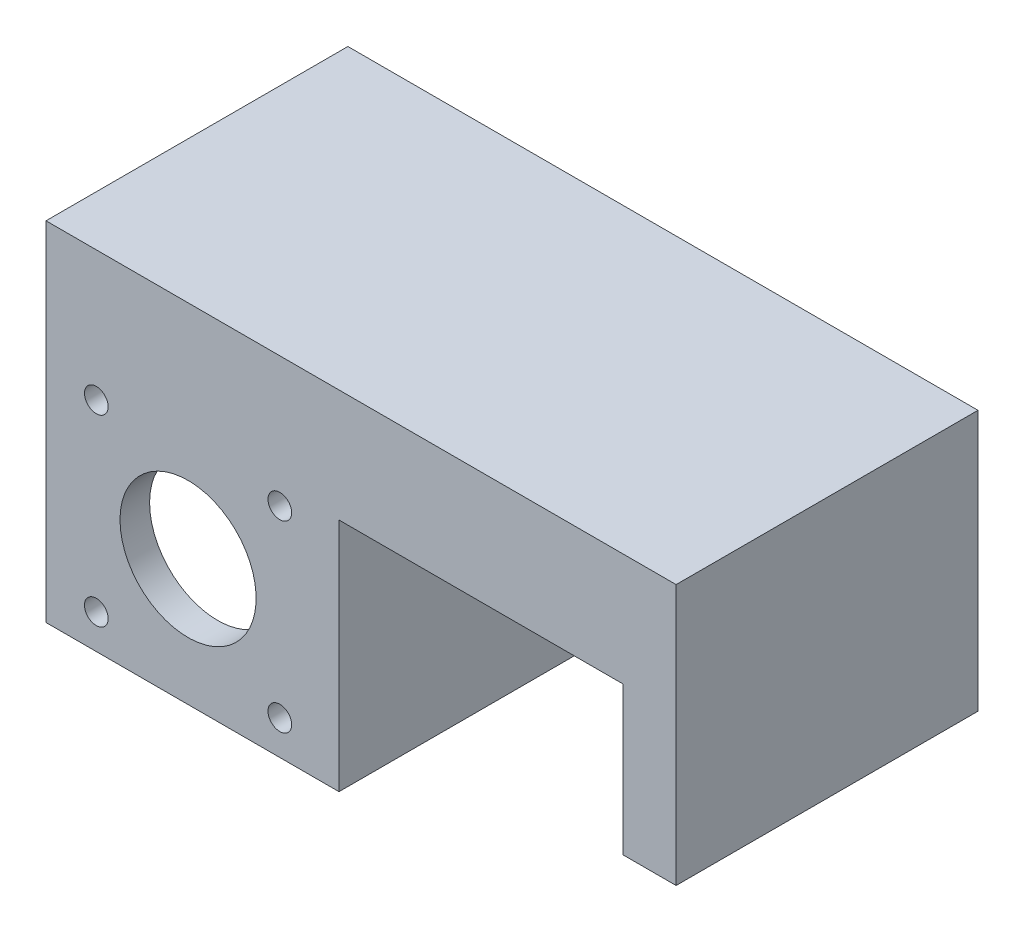
SolidWorks part; units mm, degrees
ref_plane "Front Plane" through (0, 0, 0) normal (0, 0, 1) x (1, 0, 0)
ref_plane "Top Plane" through (0, 0, 0) normal (0, 1, 0) x (1, 0, 0)
ref_plane "Right Plane" through (0, 0, 0) normal (1, 0, 0) x (0, 0, -1)
sketch "Sketch1" plane through (0, 0, 0) normal (0, 0, 1) x (1, 0, 0)
  line L1 (0, 0) -> (48, 0)
  line L2 (0, 0) -> (0, 53)
  line L3 (0, 53) -> (48, 53)
  line L4 (48, 0) -> (48, 53)
  dimension "D1" = 53
  dimension "D2" = 48
extrude "Boss-Extrude1" add sketch "Sketch1" along normal blind 10
sketch "Sketch2" plane through (0, 0, 0) normal (0, 0, -1) x (-1, 0, 0)
  line L0 (0, 53) -> (0, 0) construction
  line L1 (-48, 0) -> (0, 0)
  line L2 (-48, 0) -> (-48, -5.6163)
  line L3 (-48, -5.6163) -> (0, -5.6163)
  line L4 (0, 0) -> (0, -5.6163)
  dimension "D1" = 5.6163
extrude "Boss-Extrude2" add sketch "Sketch2" against normal blind 33.1918
sketch "Sketch4" plane through (0, 0, 10) normal (0, 0, 1) x (1, 0, 0)
  line L1 (0, 53) -> (4, 53)
  line L2 (0, 53) -> (0, 43)
  line L3 (0, 43) -> (4, 43)
  line L4 (4, 53) -> (4, 43)
  line L5 (48, 53) -> (44, 53)
  line L6 (48, 53) -> (48, 43)
  line L7 (48, 43) -> (44, 43)
  line L8 (44, 53) -> (44, 43)
  dimension "D1" = 10
  dimension "D2" = 4
extrude "Boss-Extrude4" add sketch "Sketch4" along normal blind 40
sketch "Sketch5" plane through (0, 0, 10) normal (0, 0, 1) x (1, 0, 0)
  line L0 (48, 0) -> (48, 43) construction
  line L1 (0, 0) -> (48, 0)
  line L2 (0, 0) -> (0, 10.8609)
  line L3 (0, 10.8609) -> (48, 10.8609)
  line L4 (48, 0) -> (48, 10.8609)
  dimension "D1" = 10.8609
extrude "Boss-Extrude5" add sketch "Sketch5" along normal up to surface (23.1918 mm away) up to face at (24, -2.8082, 33.1918)
sketch "Sketch6" plane through (0, -5.6163, 0) normal (0, -1, 0) x (1, 0, 0)
  line L0 (0, 0) -> (0, 28.1918) construction
  line L1 (0, 33.1918) -> (0, 0) construction
  line L2 (48, 33.1918) -> (48, 0) construction
  line L3 (0, 28.1918) -> (48, 28.1918)
  line L4 (0, 28.1918) -> (0, 33.1918)
  line L5 (0, 33.1918) -> (48, 33.1918)
  line L6 (48, 28.1918) -> (48, 33.1918)
  line L8 (48, 33.1918) -> (0, 33.1918) construction
  dimension "D2" = 5
extrude "Boss-Extrude6" add sketch "Sketch6" along normal blind 42.3
sketch "Sketch7" plane through (0, 0, 0) normal (-1, 0, 0) x (0, 0, 1)
  line L0 (33.1918, 10.8609) -> (10, 10.8609) construction
  line L1 (0, -5.6163) -> (-12.8082, -5.6163)
  line L2 (0, -5.6163) -> (0, 10.8609)
  line L3 (0, 10.8609) -> (-12.8082, 10.8609)
  line L4 (-12.8082, -5.6163) -> (-12.8082, 10.8609)
  line L5 (28.1918, -47.9163) -> (28.1918, -5.6163) construction
  dimension "D1" = 41
extrude "Boss-Extrude7" add sketch "Sketch7" against normal up to surface (48 mm away) up to face at (48, 10.6657, 24.2767)
sketch "Sketch8" plane through (0, 0, 28.1918) normal (0, 0, -1) x (-1, 0, 0)
  line L0 (-24, -26.6163) -> (-24, -5.6163) construction
  line L1 (0, -5.6163) -> (-48, -5.6163) construction
  line L3 (-8.5, -42.1163) -> (-39.5, -42.1163) construction
  line L4 (-8.5, -42.1163) -> (-8.5, -11.1163) construction
  line L5 (-8.5, -11.1163) -> (-39.5, -11.1163) construction
  line L6 (-39.5, -42.1163) -> (-39.5, -11.1163) construction
  line L7 (-8.5, -42.1163) -> (-39.5, -11.1163) construction
  line L8 (-8.5, -11.1163) -> (-39.5, -42.1163) construction
  circle A0 centre (-24, -26.6163) radius 11.5
  circle A1 centre (-39.5, -11.1163) radius 2
  circle A2 centre (-39.5, -42.1163) radius 2
  circle A3 centre (-8.5, -11.1163) radius 2
  circle A4 centre (-8.5, -42.1163) radius 2
  dimension "D2" = 23
  dimension "D4" = 4
  dimension "D1" = 21
  dimension "D3" = 31
extrude "Cut-Extrude1" cut sketch "Sketch8" against normal up to next
fillet "Fillet1" radius 10 1 edges at (24, 10.8609, 0)
fillet "Fillet2" radius 4 2 edges at (2, 43, 10) (46, 43, 10)
sketch "Sketch9" plane through (48, 0, 0) normal (1, 0, 0) x (0, 0, -1)
  line L1 (12.8082, 10.8609) -> (17.8082, 10.8609)
  line L2 (12.8082, 10.8609) -> (12.8082, -5.6163)
  line L3 (12.8082, -5.6163) -> (17.8082, -5.6163)
  line L4 (17.8082, 10.8609) -> (17.8082, -5.6163)
  line L5 (-28.1918, -5.6163) -> (12.8082, -5.6163) construction
  dimension "D1" = 5
extrude "Boss-Extrude9" add sketch "Sketch9" against normal up to surface (48 mm away) contours L4 L3 L2 L1 up to face at (0, 13.3569, 15.8852)
sketch "Sketch10" plane through (48, 0, 0) normal (1, 0, 0) x (0, 0, -1)
  line L0 (17.8082, 10.8609) -> (-33.1918, 10.8609)
  line L1 (-33.1918, 10.8609) -> (-76.8871, 43.9021)
  line L2 (-76.8871, 43.9021) -> (-50.7941, 74.4365)
  line L3 (-50.7941, 74.4365) -> (27.2075, 71.1055)
  line L4 (27.2075, 71.1055) -> (17.8082, 10.8609)
extrude "Cut-Extrude2" cut sketch "Sketch10" against normal through all
sketch "Sketch11" plane through (48, 0, 0) normal (1, 0, 0) x (0, 0, -1)
  line L1 (-33.1918, 10.8609) -> (17.8082, 10.8609)
  line L2 (-33.1918, 10.8609) -> (-33.1918, -5.6163)
  line L3 (-33.1918, -5.6163) -> (17.8082, -5.6163)
  line L4 (17.8082, 10.8609) -> (17.8082, -5.6163)
extrude "Boss-Extrude10" add sketch "Sketch11" along normal blind 49.45
sketch "Sketch12" plane through (0, 0, 28.1918) normal (0, 0, -1) x (-1, 0, 0)
  line L0 (0, -47.9163) -> (-48, -47.9163) construction
  line L2 (-48, -5.6163) -> (-48, -47.9163) construction
  line L3 (-48, -47.9163) -> (-45, -47.9163)
  line L4 (-45, -5.6163) -> (-45, -47.9163)
  line L5 (-49.5, -5.6163) -> (-45, -5.6163)
  line L7 (-48, -5.6163) -> (-48, -47.9163) construction
  line L8 (-48, -47.9163) -> (-49.5, -47.9163)
  line L9 (-49.5, -5.6163) -> (-49.5, -47.9163)
  dimension "D1" = 3
  dimension "D2" = 1.5
extrude "Boss-Extrude11" add sketch "Sketch12" along normal up to surface (46 mm away) up to face at (48.725, 2.6223, -17.8082)
sketch "Sketch16" plane through (0, -5.6163, 0) normal (0, -1, 0) x (1, 0, 0)
  line L1 (49.5, -17.8082) -> (97.45, -17.8082)
  line L2 (49.5, -17.8082) -> (49.5, 33.1918)
  line L3 (49.5, 33.1918) -> (97.45, 33.1918)
  line L4 (97.45, -17.8082) -> (97.45, 33.1918)
extrude "Boss-Extrude14" add sketch "Sketch16" along normal blind 2.55
sketch "Sketch14" plane through (49.5, 0, 0) normal (1, 0, 0) x (0, 0, -1)
  line L1 (-28.1918, -5.6163) -> (-33.1918, -5.6163)
  line L2 (-28.1918, -5.6163) -> (-28.1918, -47.9163)
  line L3 (-28.1918, -47.9163) -> (-33.1918, -47.9163)
  line L4 (-33.1918, -5.6163) -> (-33.1918, -47.9163)
extrude "Boss-Extrude13" add sketch "Sketch14" against normal up to surface (1.5 mm away) up to face at (48, -26.7663, 30.6918)
sketch "Sketch17" plane through (97.45, 0, 0) normal (1, 0, 0) x (0, 0, -1)
  line L1 (-33.1918, -8.1663) -> (17.8082, -8.1663)
  line L2 (-33.1918, -8.1663) -> (-33.1918, 10.8609)
  line L3 (-33.1918, 10.8609) -> (17.8082, 10.8609)
  line L4 (17.8082, -8.1663) -> (17.8082, 10.8609)
extrude "Boss-Extrude15" add sketch "Sketch17" along normal blind 9
sketch "Sketch18" plane through (0, -8.1663, 0) normal (0, -1, 0) x (1, 0, 0)
  line L0 (106.45, 33.1918) -> (106.45, -17.8082) construction
  line L1 (49.5, -17.8082) -> (106.45, -17.8082)
  line L2 (49.5, -17.8082) -> (49.5, -9.8082)
  line L3 (49.5, -9.8082) -> (97.45, -9.8082)
  line L4 (106.45, -17.8082) -> (106.45, -9.8082)
  line L5 (106.45, 33.1918) -> (49.5, 33.1918) construction
  line L7 (106.45, -9.8082) -> (106.45, 33.1918)
  line L8 (106.45, 33.1918) -> (97.45, 33.1918)
  line L9 (97.45, -9.8082) -> (97.45, 33.1918)
  dimension "D1" = 9
  dimension "D2" = 8
extrude "Boss-Extrude16" add sketch "Sketch18" along normal blind 25
sketch "Sketch19" plane through (0, 0, -9.8082) normal (0, 0, 1) x (1, 0, 0)
  line L0 (49.5, -8.1663) -> (58.475, -26.1663) construction
  line L1 (58.475, -26.1663) -> (88.475, -26.1663) construction
  line L2 (88.475, -26.1663) -> (97.45, -8.1663) construction
  line L3 (97.45, -8.1663) -> (49.5, -8.1663) construction
  circle A0 centre (58.475, -26.1663) radius 1.9304
  circle A1 centre (88.475, -26.1663) radius 1.9304
  dimension "D3" = 3.8608
  dimension "D1" = 30
  dimension "D2" = 18
extrude "Cut-Extrude3" cut sketch "Sketch19" against normal through all
